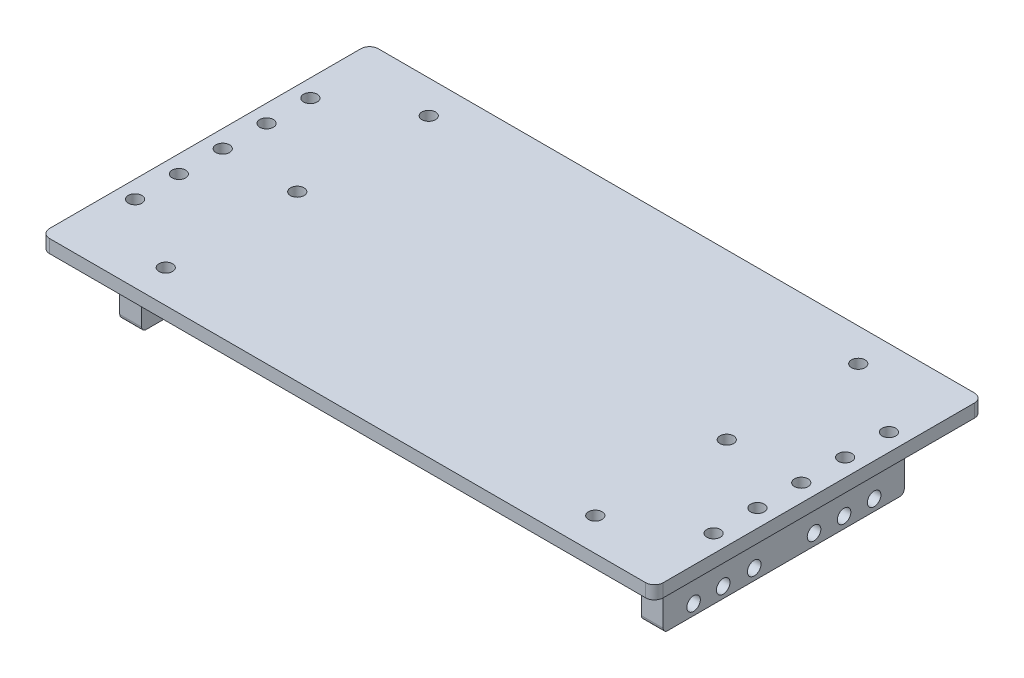
SolidWorks part; units mm, degrees
ref_plane "前视基准面" through (0, 0, 0) normal (0, 0, 1) x (1, 0, 0)
ref_plane "上视基准面" through (0, 0, 0) normal (0, 1, 0) x (1, 0, 0)
ref_plane "右视基准面" through (0, 0, 0) normal (1, 0, 0) x (0, 0, -1)
other "Configuration Table"
sketch "草图1" plane through (0, 0, 0) normal (0, 1, 0) x (1, 0, 0)
  line L0 (-70, 37.5) -> (70, 37.5)
  line L1 (70, 37.5) -> (70, -37.5)
  line L2 (70, -37.5) -> (-70, -37.5)
  line L3 (-70, -37.5) -> (-70, 37.5)
  line L4 (-70, 30) -> (-49, 30) construction
  line L5 (-70, 37.5) -> (70, -37.5) construction
  line L6 (-70, -37.5) -> (70, 37.5) construction
  line L7 (-49, 30) -> (-49, 37.5) construction
  line L8 (-49, 30) -> (-49, 0) construction
  line L9 (-49, 0) -> (-49, -30) construction
  line L10 (0, -55) -> (0, 55) construction
  line L11 (49, 30) -> (49, 0) construction
  line L12 (49, 0) -> (49, -30) construction
  point P2 (-55, 37.5)
  point P5 (-70, 30)
  point P6 (-49, 37.5)
  point P7 (0, 0)
  point P8 (-49, 30)
  point P10 (-49, 0)
  point P11 (-49, -30)
  dimension "D1" = 140
  dimension "D2" = 75
  dimension "D3" = 7.5
  dimension "D4" = 15
  dimension "D5" = 6
  dimension "D6" = 30
  dimension "D7" = 30
extrude "凸台-拉伸1" add sketch "草图1" along normal blind 3 contours L3 L0 L1 L2
sketch "草图2" plane through (0, 0, 0) normal (0, -1, 0) x (1, 0, 0)
  line L0 (-49, -30) -> (-49, 0) construction
  line L1 (-49, 0) -> (-49, 30) construction
  line L2 (49, -30) -> (49, 0) construction
  line L3 (49, 0) -> (49, 30) construction
  line L4 (-49, -30) -> (-49, 0) construction
  line L5 (-49, 0) -> (-49, 30) construction
  line L6 (49, -30) -> (49, 0) construction
  line L7 (49, 0) -> (49, 30) construction
  circle A0 centre (-49, 0) radius 1.55
  circle A1 centre (-49, -30) radius 1.55
  circle A2 centre (-49, 30) radius 1.55
  circle A3 centre (49, 30) radius 1.55
  circle A4 centre (49, 0) radius 1.55
  circle A5 centre (49, -30) radius 1.55
extrude "切除-拉伸1" cut sketch "草图2" against normal blind 3
sketch "草图3" plane through (0, 0, 0) normal (0, -1, 0) x (1, 0, 0)
  line L0 (-70, 37.5) -> (-70, -37.5) construction
  line L1 (70, 37.5) -> (-70, 37.5) construction
  line L2 (-70, -37.5) -> (70, -37.5) construction
  line L3 (0, -1.65) -> (0, 1.65) construction
  line L12 (-62, 27.5) -> (-62, -27.5)
  line L13 (-62, -27.5) -> (-57, -27.5)
  line L14 (-57, -27.5) -> (-57, 27.5)
  line L15 (-57, 27.5) -> (-62, 27.5)
  line L16 (57, -27.5) -> (57, 27.5)
  line L17 (62, -27.5) -> (57, -27.5)
  line L18 (62, 27.5) -> (62, -27.5)
  line L19 (57, 27.5) -> (62, 27.5)
  point P0 (-70, 27.5)
  point P5 (-70, -27.5)
  point P8 (-62, 27.5)
  point P11 (70, -27.5)
  point P12 (70, 27.5)
  point P15 (-62, -27.5)
  dimension "D1" = 10
  dimension "D2" = 10
  dimension "D3" = 8
  dimension "D4" = 8
  dimension "D5" = 10
  dimension "D6" = 55
  dimension "D7" = 5
extrude "凸台-拉伸2" add sketch "草图3" along normal blind 15
sketch "草图5" plane through (0, 0, 0) normal (0, -1, 0) x (1, 0, 0)
  line L0 (-62, 27.5) -> (-62, 37.5) construction
  line L1 (70, 37.5) -> (-70, 37.5) construction
  line L2 (-70, 37.5) -> (-70, -37.5) construction
  line L3 (-70, 27.5) -> (-62, 27.5) construction
  line L4 (9.9, 0) -> (-9.9, 0) construction
  line L5 (-70, -27.5) -> (-62, -27.5) construction
  line L6 (-66, 20) -> (-66, 0) construction
  line L7 (-66, 0) -> (-66, -20) construction
  line L8 (0, -9.9) -> (0, 9.9) construction
  line L9 (66, 0) -> (66, -20) construction
  line L10 (66, 20) -> (66, 0) construction
  circle A0 centre (-66, 20) radius 1.55
  circle A1 centre (-66, 10) radius 1.55
  circle A2 centre (-66, 0) radius 1.55
  circle A3 centre (-66, -10) radius 1.55
  circle A4 centre (-66, -20) radius 1.55
  circle A5 centre (66, -20) radius 1.55
  circle A6 centre (66, -10) radius 1.55
  circle A7 centre (66, 0) radius 1.55
  circle A8 centre (66, 10) radius 1.55
  circle A9 centre (66, 20) radius 1.55
  point P5 (-70, 27.5)
  point P13 (-66, 27.5)
  point P14 (-66, 20)
  point P15 (-66, 0)
  point P16 (-66, -20)
  point P17 (-66, 10)
  point P20 (-66, -10)
  point P41 (66, -10)
  point P42 (66, 10)
  point P43 (66, -20)
  point P44 (66, 0)
  point P45 (66, 20)
  dimension "D1" = 55
  dimension "D2" = 20
extrude "切除-拉伸2" cut sketch "草图5" against normal blind 15
sketch "草图6" plane through (-62, 0, 0) normal (-1, 0, 0) x (0, 0, 1)
  line L0 (-27.5, -15) -> (-27.5, 0) construction
  line L1 (-27.5, -7.5) -> (-27.5, -15) construction
  line L2 (0, -9.9) -> (0, 9.9) construction
  line L3 (27.5, -15) -> (27.5, 0) construction
  line L4 (-27.5, -11.25) -> (27.5, -11.25) construction
  line L5 (-27.5, -15) -> (0, -15) construction
  line L6 (27.5, -15) -> (-27.5, -15) construction
  line L7 (0, -15) -> (27.5, -15) construction
  line L8 (-18.9754, -11.25) -> (-18.9754, -15) construction
  line L9 (-27.5, -15) -> (-27.5, -22.7806) construction
  line L10 (-27.5, -22.7806) -> (-13.75, -22.7806) construction
  line L11 (-13.75, -22.7806) -> (-13.75, -15) construction
  line L12 (-20.625, -22.7806) -> (-20.625, -15) construction
  line L13 (-13.75, -22.7806) -> (0, -22.7806) construction
  line L14 (0, -22.7806) -> (0, -15) construction
  line L15 (-20.625, -12.5) -> (-20.625, -15) construction
  circle A0 centre (-20.625, -12.5) radius 1.55
  circle A1 centre (-13.7668, -12.4633) radius 1.55
  circle A2 centre (-6.9115, -12.401) radius 1.55
  circle A3 centre (6.7368, -12.4945) radius 1.55
  circle A4 centre (13.8102, -12.5568) radius 1.55
  circle A5 centre (20.572, -12.588) radius 1.55
  point P0 (-27.5, -7.5)
  point P1 (-27.5, -15)
  point P7 (-27.5, -11.25)
  point P8 (0, -11.25)
  point P9 (27.5, -11.25)
  point P16 (0, -11.25)
  point P17 (-13.75, -15)
  point P18 (-27.5, -11.25)
  point P23 (13.75, -15)
  point P26 (-18.9754, -13.125)
  point P27 (-20.625, -22.7806)
  point P33 (-6.875, -15)
  point P34 (-20.625, -12.5)
  point P36 (-6.875, -22.7806)
  point P37 (-13.75, -12.5)
  point P38 (-6.875, -12.5)
  point P39 (0, -13.125)
  point P40 (0, 0)
  point P41 (6.875, -12.5)
  point P42 (13.75, -12.5)
  point P43 (20.625, -12.5)
  point P46 (-20.625, -15)
  point P47 (-20.625, -12.5)
  point P48 (0, 0)
  point P51 (0, 0)
  point P54 (0, 0)
  point P57 (0, 0)
  point P60 (0, 0)
  dimension "D1" = 2.5
extrude "切除-拉伸3" cut sketch "草图6" against normal blind 15
mirror "镜向1" about plane through (0, 0, 0) normal (1, 0, 0) of "切除-拉伸3"
fillet "圆角1" radius 2 4 edges at (-70, 1.5, 37.5) (-70, 1.5, -37.5) (70, 1.5, 37.5) (70, 1.5, -37.5)
fillet "圆角2" radius 1 12 edges at (59.5, -15, -27.5) (59.5, -15, 27.5) (-59.5, -15, 27.5) (-59.5, -15, -27.5) (62, 0, 0) (59.5, 0, -27.5) (57, 0, 0) (59.5, 0, 27.5) (-59.5, 0, 27.5) (-62, 0, 0) (-57, 0, 0) (-59.5, 0, -27.5)
